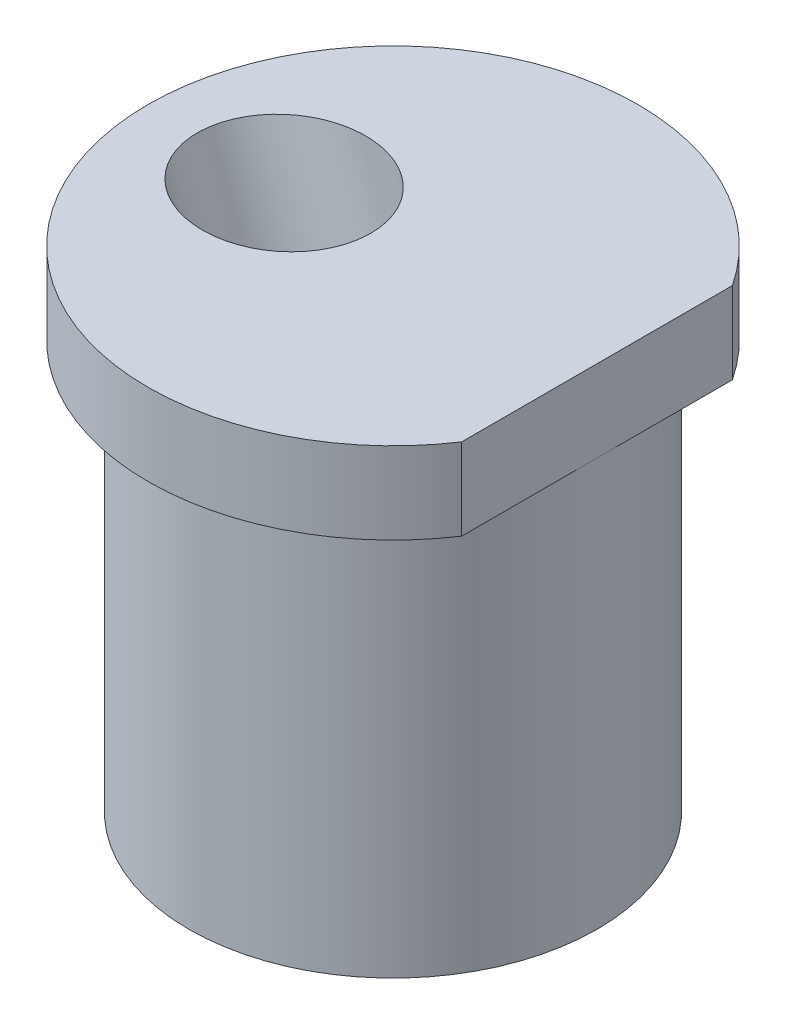
SolidWorks part; units mm, degrees
ref_plane "Front Plane" through (0, 0, 0) normal (0, 0, 1) x (1, 0, 0)
ref_plane "Top Plane" through (0, 0, 0) normal (0, 1, 0) x (1, 0, 0)
ref_plane "Right Plane" through (0, 0, 0) normal (1, 0, 0) x (0, 0, -1)
sketch "Sketch1" plane through (0, 0, 0) normal (0, 0, 1) x (1, 0, 0)
  line L0 (0, 0) -> (0, 60)
  line L1 (25, 50) -> (25, 0)
  line L2 (0, 0) -> (25, 0)
  line L3 (0, 60) -> (30, 60)
  line L4 (30, 60) -> (30, 50)
  line L5 (30, 50) -> (25, 50)
revolve "Revolve1" add sketch "Sketch1" angle 360 about L0
sketch "Sketch4" plane through (0, 60, 0) normal (0, 1, 0) x (1, 0, 0)
  line L1 (25, 25.7853) -> (44.506, 25.7853)
  line L2 (25, 25.7853) -> (25, -26.4978)
  line L3 (25, -26.4978) -> (44.506, -26.4978)
  line L4 (44.506, 25.7853) -> (44.506, -26.4978)
  dimension "D1" = 25
extrude "Cut-Extrude1" cut sketch "Sketch4" against normal blind 18
sketch "Sketch5" plane through (0, 0, 0) normal (0, 0, 1) x (1, 0, 0)
  line L0 (-23.7567, 88.6245) -> (16.9007, -23.0807)
  line L3 (-23.7567, 88.6245) -> (-16.2391, 91.3607)
  line L4 (16.9007, -23.0807) -> (24.4182, -20.3446)
  line L5 (-16.2391, 91.3607) -> (24.4182, -20.3446)
  point P1 (-23.7567, 88.6245)
  point P5 (16.9007, -23.0807)
revolve "Cut-Revolve1" cut sketch "Sketch5" angle 360 about L0
sketch "Sketch6" plane through (0, 0, 0) normal (0, 0, 1) x (1, 0, 0)
  line L0 (-9.6937, 50) -> (-17.7922, 72.2503)
  line L2 (-25, 50) -> (25, 50) construction
  line L5 (-17.7922, 72.2503) -> (-8.3953, 75.6705)
  line L6 (-8.3953, 75.6705) -> (-0.2968, 53.4202)
  line L7 (-9.6937, 50) -> (-9.0097, 48.1206)
  line L8 (-0.2968, 53.4202) -> (0.3872, 51.5408)
  line L9 (-9.0097, 48.1206) -> (0.3872, 51.5408)
  point P5 (-9.6937, 50)
  dimension "D1" = 70
revolve "Cut-Revolve2" cut sketch "Sketch6" angle 360 about L0
